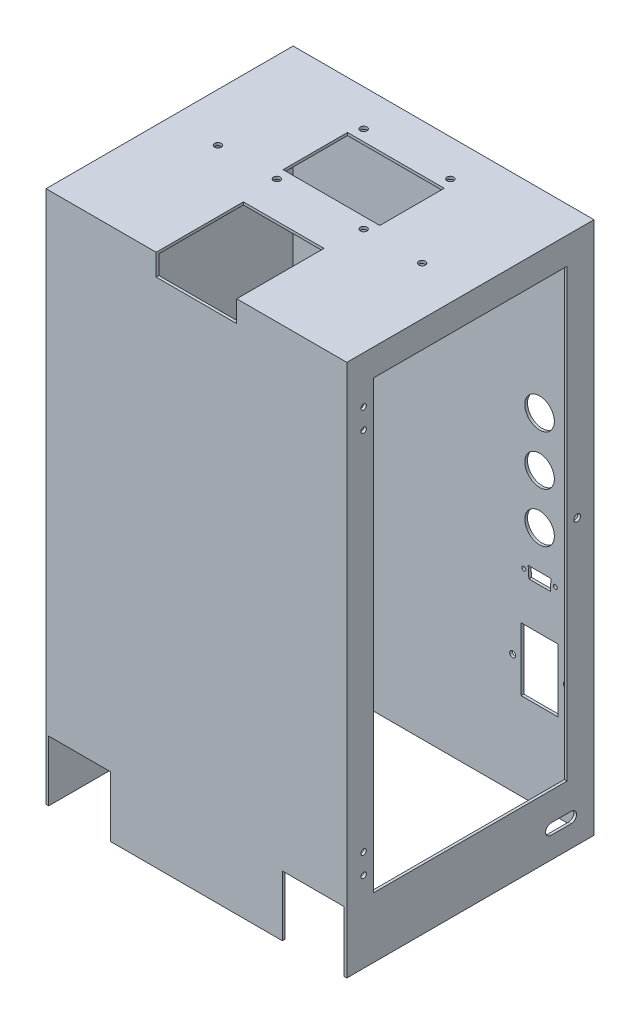
SolidWorks part; units mm, degrees
ref_plane "前视基准面" through (0, 0, 0) normal (0, 0, 1) x (1, 0, 0)
ref_plane "上视基准面" through (0, 0, 0) normal (0, 1, 0) x (1, 0, 0)
ref_plane "右视基准面" through (0, 0, 0) normal (1, 0, 0) x (0, 0, -1)
other "Configuration Table"
sketch "草图1" plane through (0, 0, 0) normal (0, 1, 0) x (1, 0, 0)
  line L0 (0, 0) -> (0, -180)
  line L7 (0, 0) -> (220, 0)
  line L9 (-2, 0) -> (-2, -182) construction
  line L10 (0, 2) -> (-11.9814, 2) construction
  line L11 (1094, -262) -> (222, -262) construction
  line L12 (47, 896) -> (47, -182) construction
  line L13 (50.4581, -182) -> (47.1016, -182) construction
  line L14 (173, -1264) -> (173, -262) construction
  line L15 (222, 2) -> (222, -182)
  line L17 (222, 2) -> (-2, 2)
  line L18 (-2, 2) -> (-2, -182)
  line L20 (47, -182) -> (173, -182)
  line L25 (47, -182) -> (-2, -182)
  line L26 (-2, -262) -> (-21.3818, -262) construction
  line L27 (47, -262) -> (47, -1265.0589) construction
  line L28 (-2, -262) -> (-2, -1503.7925) construction
  line L29 (0, -180) -> (220, -180)
  line L30 (173, -182) -> (222, -182)
  line L31 (220, -180) -> (220, 0)
  line L32 (173, -182) -> (173, 818) construction
  line L33 (173, -262) -> (47, -262) construction
extrude "凸台-拉伸1" add sketch "草图1" along normal blind 395
sketch "草图17" plane through (0, 0, 182) normal (0, 0, 1) x (1, 0, 0)
  line L0 (0, 0) -> (0, 45)
  line L1 (-2, 0) -> (222, 0) construction
  line L2 (-2, 395) -> (-2, 0) construction
  line L3 (0, 45) -> (46, 45)
  line L4 (46, 45) -> (46, 0)
  line L5 (46, 0) -> (0, 0)
  line L6 (110, 0) -> (110, 47.3457) construction
  line L7 (174, 0) -> (220, 0)
  line L8 (174, 45) -> (174, 0)
  line L9 (220, 45) -> (174, 45)
  line L10 (220, 0) -> (220, 45)
  dimension "D1" = 2
extrude "切除-拉伸2" cut sketch "草图17" against normal blind 2
sketch "草图19" plane through (0, 395, 0) normal (0, 1, 0) x (1, 0, 0)
  line L0 (-2, 2) -> (222, 2)
  line L1 (222, 2) -> (222, -182)
  line L2 (222, -182) -> (-2, -182)
  line L3 (-2, -182) -> (-2, 2)
extrude "凸台-拉伸13" add sketch "草图19" along normal blind 2
sketch "草图20" plane through (0, 0, 182) normal (0, 0, 1) x (1, 0, 0)
  line L0 (110, 397) -> (110, 370.2686) construction
  line L2 (110, 399) -> (134.2474, 399) construction
  line L3 (-2, 397) -> (222, 397) construction
  line L4 (80, 399) -> (80, 381)
  line L5 (80, 381) -> (140, 381)
  line L6 (80, 399) -> (140, 399)
  line L7 (140, 399) -> (140, 381)
  dimension "D1" = 2
  dimension "D2" = 30
extrude "切除-拉伸4" cut sketch "草图20" against normal blind 65
sketch "草图21" plane through (222, 0, 0) normal (1, 0, 0) x (0, 0, -1)
  line L0 (-182, 45) -> (2, 45) construction
  line L1 (-182, 397) -> (-182, 0) construction
  line L2 (2, 397) -> (2, 0) construction
  line L3 (-182, 0) -> (2, 0) construction
  line L4 (-162, 45) -> (-162, 377)
  line L5 (-162, 377) -> (-18, 377)
  line L6 (-182, 397) -> (2, 397) construction
  line L7 (-18, 377) -> (-18, 45)
  line L8 (-18, 45) -> (-162, 45)
  dimension "D1" = 45
  dimension "D2" = 20
  dimension "D3" = 20
extrude "切除-拉伸5" cut sketch "草图21" against normal blind 2
sketch "草图22" plane through (0, 397, 0) normal (0, 1, 0) x (1, 0, 0)
  line L1 (222, 2) -> (-2, 2) construction
  line L2 (71.7, -57.5) -> (71.7, -95.8) construction
  line L4 (72.5, 2) -> (147.5, 2) construction
  line L6 (140, -117) -> (140, 2) construction
  line L17 (129.5716, -57.5) -> (92.0716, -57.5) construction
  line L25 (71.7, -95.8) -> (148.3, -95.8) construction
  line L26 (148.3, -95.8) -> (148.3, -19.2) construction
  line L27 (148.3, -19.2) -> (71.7, -19.2) construction
  line L28 (71.7, -19.2) -> (71.7, -57.5) construction
  line L29 (74, -57.5) -> (74, -81.5)
  line L30 (74, -81.5) -> (146, -81.5)
  line L31 (146, -81.5) -> (146, -33.5)
  line L32 (146, -33.5) -> (74, -33.5)
  line L33 (74, -33.5) -> (74, -57.5)
  circle A0 centre (77.7, -25.2) radius 2.5
  circle A1 centre (77.7, -89.8) radius 2.5
  circle A2 centre (142.3, -89.8) radius 2.5
  circle A3 centre (142.3, -25.2) radius 2.5
  point P19 (142.3, -25.2)
  point P21 (142.3, -89.8)
  point P22 (77.7, -89.8)
  dimension "D3" = 6
  dimension "D5" = 6
  dimension "D1" = 6
  dimension "D2" = 2.3
  dimension "D4" = 6
  dimension "D6" = 6
  dimension "D7" = 6
  dimension "D8" = 6
  dimension "D9" = 6
extrude "切除-拉伸6" cut sketch "草图22" against normal blind 10
sketch "草图23" plane through (0, 0, -2) normal (0, 0, -1) x (-1, 0, 0)
  line L0 (-222, 50) -> (2, 50) construction
  line L1 (-222, 397) -> (-222, 0) construction
  line L2 (2, 397) -> (2, 0) construction
  line L4 (-202, 50) -> (-202, 112.1441) construction
  line L5 (-110, 50) -> (-110, 16.8353) construction
  line L6 (-165, 50) -> (-165, 95.6657) construction
  line L7 (-183.5, 59.3099) -> (-203.5, 59.3099) construction
  line L8 (-183.5, 54.0811) -> (-183.5, 78.8528) construction
  line L9 (-203.5, 59.3099) -> (-203.5, 117.6099) construction
  line L10 (-203.5, 117.6099) -> (-163.5, 117.6099) construction
  line L11 (-163.5, 117.6099) -> (-163.5, 59.3099) construction
  line L12 (-163.5, 59.3099) -> (-183.5, 59.3099) construction
  line L21 (-199, 138.1099) -> (-183.5, 138.1099) construction
  line L26 (-203.5, 88.4599) -> (-163.5, 88.4599) construction
  line L27 (-199, 138.1099) -> (-199, 154.1099) construction
  line L28 (-183.5, 111.9599) -> (-197.25, 111.9599)
  line L29 (-197.25, 111.9599) -> (-197.25, 64.9599)
  line L30 (-197.25, 64.9599) -> (-169.75, 64.9599)
  line L31 (-169.75, 64.9599) -> (-169.75, 111.9599)
  line L32 (-169.75, 111.9599) -> (-183.5, 111.9599)
  line L33 (-199, 154.1099) -> (-168, 154.1099) construction
  line L34 (-168, 154.1099) -> (-168, 138.1099) construction
  line L35 (-168, 138.1099) -> (-183.5, 138.1099) construction
  line L36 (-183.5, 151.6099) -> (-175, 151.6099)
  line L37 (-183.5, 143.1099) -> (-175.5, 143.1099)
  line L38 (-183.5, 151.6099) -> (-192, 151.6099)
  line L39 (-183.5, 143.1099) -> (-191.5, 143.1099)
  line L40 (-192, 151.6099) -> (-191.5, 143.1099)
  line L41 (-175.5, 143.1099) -> (-175, 151.6099)
  line L43 (-168, 147.8599) -> (-175, 147.8599) construction
  circle A0 centre (-183.5, 217.1099) radius 11
  circle A1 centre (-203.5, 88.4599) radius 2.25
  circle A2 centre (-163.5, 88.4599) radius 2.25
  circle A3 centre (-183.5, 180.1099) radius 11
  circle A4 centre (-183.5, 254.1099) radius 11
  circle A5 centre (-171.8, 147.8599) radius 1.5
  circle A6 centre (-195.2, 147.8599) radius 1.5
  dimension "D3" = 26
  dimension "D4" = 20.5
  dimension "D6" = 37
  dimension "D10" = 3.8
  dimension "D1" = 20
  dimension "D2" = 55
  dimension "D5" = 37
  dimension "D7" = 13.5
  dimension "D8" = 11
  dimension "D9" = 24
extrude "切除-拉伸7" cut sketch "草图23" against normal blind 2
sketch "草图24" plane through (222, 0, 0) normal (1, 0, 0) x (0, 0, -1)
  line L0 (-18, 377) -> (-162, 377) construction
  line L1 (-162, 377) -> (-162, 45) construction
  line L2 (-163.6677, 211) -> (-19.6677, 211) construction
  line L4 (-18, 45) -> (-18, 377) construction
  circle A0 centre (-169.5, 362) radius 2
  circle A1 centre (-169.5, 347) radius 2
  circle A2 centre (-169.5, 75) radius 2
  circle A3 centre (-169.5, 60) radius 2
  circle A4 centre (-10.5, 211) radius 2.5
  dimension "D1" = 15
  dimension "D3" = 15
  dimension "D4" = 7.5
  dimension "D2" = 7.5
extrude "切除-拉伸8" cut sketch "草图24" against normal blind 3
sketch "草图25" plane through (222, 0, 0) normal (1, 0, 0) x (0, 0, -1)
  line L0 (-182, 40) -> (2, 40) construction
  line L1 (-182, 397) -> (-182, 0) construction
  line L2 (2, 397) -> (2, 0) construction
  line L4 (-182, 40) -> (-182, 0) construction
  line L5 (-182, 0) -> (2, 0) construction
  line L6 (2, 0) -> (2, 40) construction
  line L7 (-182, 20) -> (2, 20) construction
  line L8 (-15, 16) -> (-30, 16)
  line L9 (-30, 24) -> (-15, 24)
  arc A0 (-15, 16) -> (-15, 24) centre (-15, 20) ccw
  arc A1 (-30, 24) -> (-30, 16) centre (-30, 20) ccw
  dimension "D2" = 15
  dimension "D1" = 17
extrude "切除-拉伸9" cut sketch "草图25" against normal through all
hole_wizard "M6 螺纹孔1" positions "草图26" profile "草图27" tap size "M6" standard "GB" end condition through all
sketch "草图26" plane through (0, 397, 0) normal (0, 1, 0) x (1, 0, 0)
  line L0 (-2, -90) -> (222, -90) construction
  line L1 (-2, 2) -> (-2, -182) construction
  line L2 (222, -182) -> (222, 2) construction
  line L4 (110, -90) -> (110, -102.0992) construction
  point P19 (34, -90)
  point P22 (186, -90)
  dimension "D1" = 76
sketch "草图27" plane through (186, 397, 90) normal (1, 0, 0) x (0, 0, 1)
  line L0 (0, 0) -> (0, 397)
  line L1 (0, 397) -> (2.5, 397)
  line L2 (2.5, 397) -> (2.5, 0)
  line L5 (2.5, 0) -> (0, 0)
  line L11 (0, -6.35) -> (0, 107.95) construction
  dimension "通孔螺纹孔钻头直径" = 5
  dimension "通孔螺纹孔钻头深度" = 397
cosmetic thread "孔螺蚊线1" parameters "D2"=6
cosmetic thread "孔螺蚊线2" parameters "D2"=6
